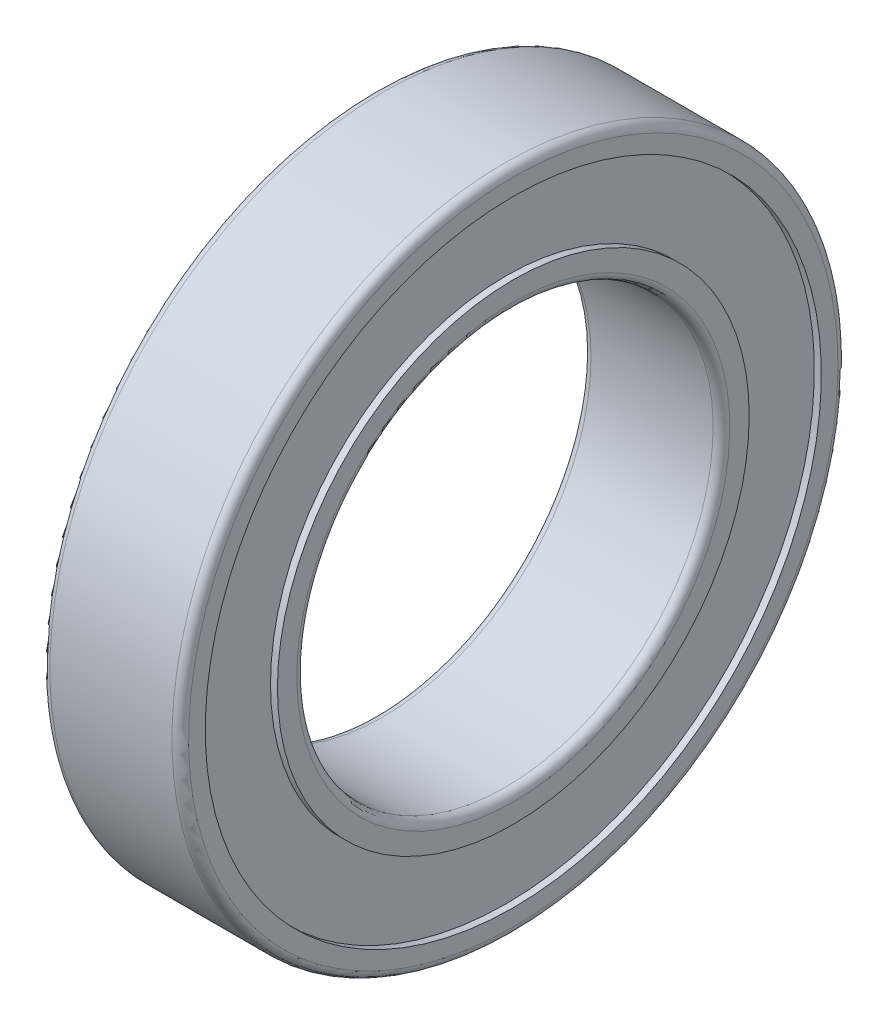
SolidWorks part; units mm, degrees
ref_plane "Front Plane" through (0, 0, 0) normal (0, 0, 1) x (1, 0, 0)
ref_plane "Top Plane" through (0, 0, 0) normal (0, 1, 0) x (1, 0, 0)
ref_plane "Right Plane" through (0, 0, 0) normal (1, 0, 0) x (0, 0, -1)
sketch "Sketch1" plane through (0, 0, 0) normal (0, 0, 1) x (1, 0, 0)
  line L0 (0, 0) -> (5, 0) construction
  line L1 (0, 7.5) -> (0, 8.5)
  line L2 (0, 8.5) -> (0.25, 8.5)
  line L3 (0.25, 8.5) -> (0.25, 11.1)
  line L4 (0.25, 11.1) -> (0, 11.1)
  line L5 (0, 11.1) -> (0, 12)
  line L6 (0, 12) -> (5, 12)
  line L7 (5, 12) -> (5, 11.1)
  line L8 (5, 11.1) -> (4.75, 11.1)
  line L9 (4.75, 11.1) -> (4.75, 8.5)
  line L10 (4.75, 8.5) -> (5, 8.5)
  line L11 (5, 8.5) -> (5, 7.5)
  line L12 (5, 7.5) -> (0, 7.5)
  dimension "D_s" = 15
  dimension "D" = 24
  dimension "B" = 5
  dimension "MSM_3" = 17
  dimension "MSM_4" = 22.2
  dimension "MSM_5" = 4.5
revolve "Revolve1" add sketch "Sketch1" angle 360 about L0
fillet "Fillet1" radius 0.3 4 edges at (0, -7.5, 0) (5, -7.5, 0) (0, -12, 0) (5, -12, 0)
